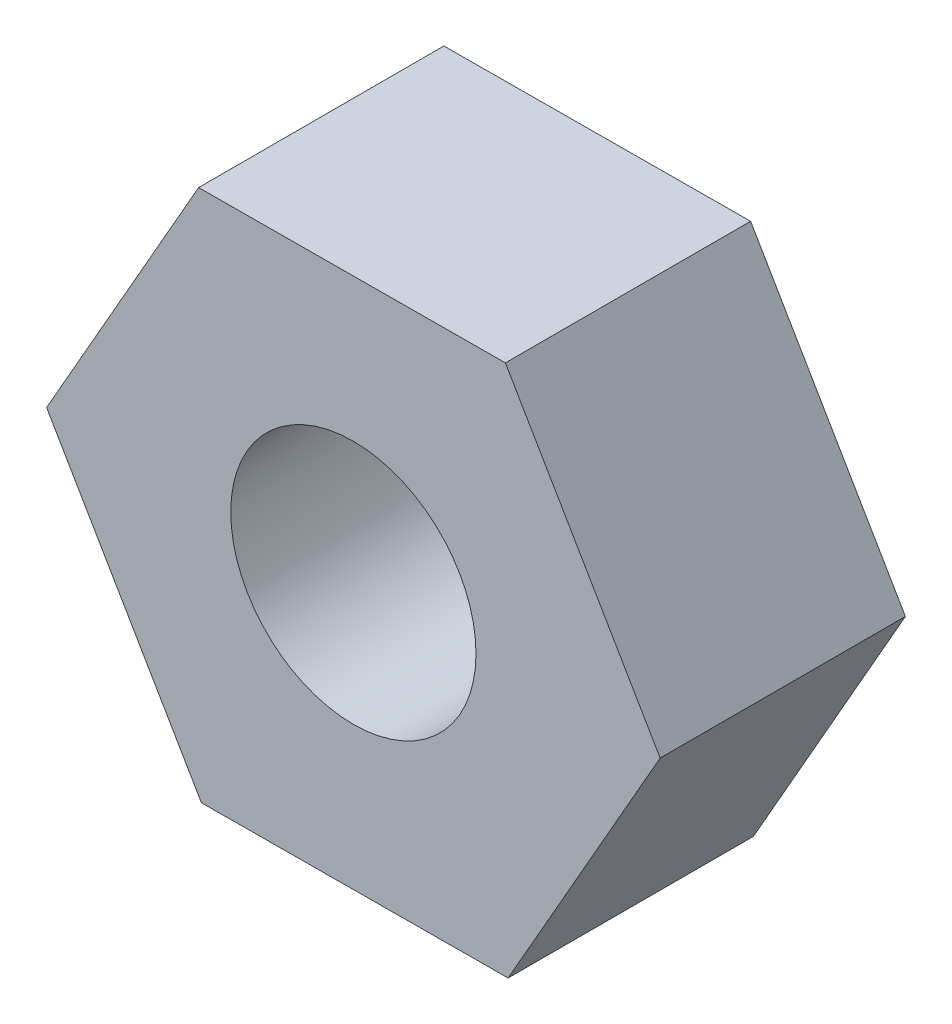
SolidWorks part; units mm, degrees
ref_plane "Front Plane" through (0, 0, 0) normal (0, 0, 1) x (1, 0, 0)
ref_plane "Top Plane" through (0, 0, 0) normal (0, 1, 0) x (1, 0, 0)
ref_plane "Right Plane" through (0, 0, 0) normal (1, 0, 0) x (0, 0, -1)
sketch "Sketch1" plane through (0, 0, 0) normal (0, 0, 1) x (1, 0, 0)
  line L0 (-21.0316, 20.9639) -> (-20.8958, -5.0361) construction
  line L1 (-13.3902, -4.9969) -> (-5.9526, 8.0423)
  line L2 (-5.9526, 8.0423) -> (-13.526, 21.0031)
  line L3 (-13.526, 21.0031) -> (-28.5372, 20.9246)
  line L4 (-28.5372, 20.9246) -> (-35.9748, 7.8854)
  line L5 (-35.9748, 7.8854) -> (-28.4013, -5.0754)
  line L6 (-28.4013, -5.0754) -> (-13.3902, -4.9969)
  line L7 (-35.9748, 7.8854) -> (-5.9526, 8.0423) construction
  circle A0 centre (-20.9637, 7.9639) radius 13.0002 construction
  circle A1 centre (-20.9637, 7.9639) radius 6
  dimension "D2" = 12
  dimension "D1" = 26
extrude "Boss-Extrude1" add sketch "Sketch1" against normal blind 12
